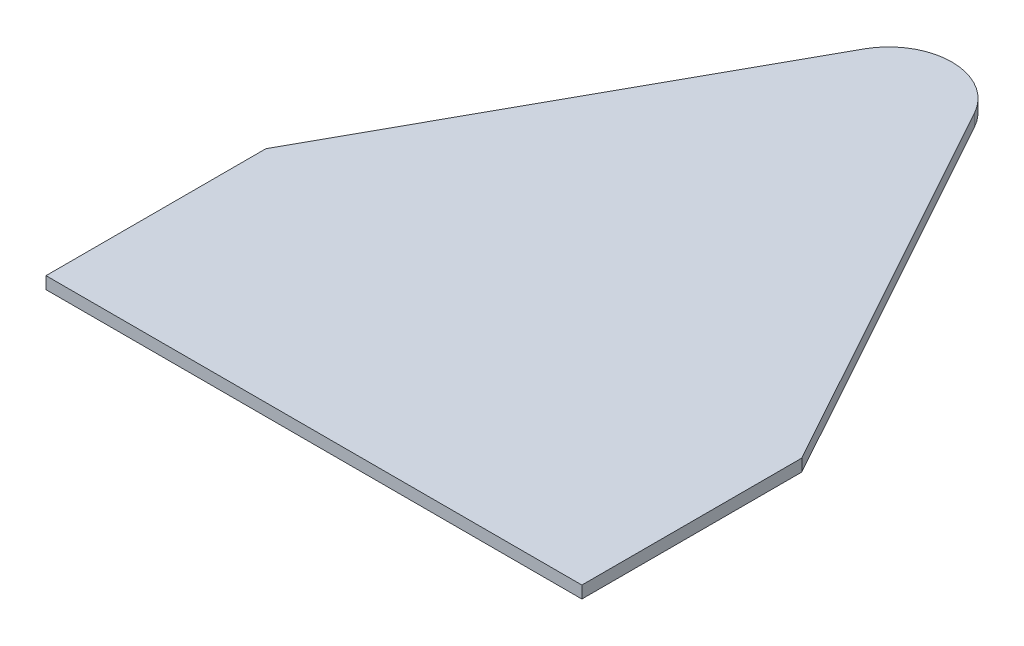
SolidWorks part; units mm, degrees
ref_plane "Front Plane" through (0, 0, 0) normal (0, 0, 1) x (1, 0, 0)
ref_plane "Top Plane" through (0, 0, 0) normal (0, 1, 0) x (1, 0, 0)
ref_plane "Right Plane" through (0, 0, 0) normal (1, 0, 0) x (0, 0, -1)
sketch "Sketch1" plane through (0, 0, 0) normal (0, 1, 0) x (1, 0, 0)
  line L0 (-11.385, 124.53) -> (-55.125, 45.25)
  line L1 (-55.125, 45.25) -> (-55.125, 0)
  line L2 (-55.125, 0) -> (55.125, 0)
  line L3 (55.125, 0) -> (55.125, 45.25)
  line L4 (55.125, 45.25) -> (11.385, 124.53)
  arc A0 (11.385, 124.53) -> (-11.385, 124.53) centre (0, 118.2545) ccw
  point P8 (0, 0)
  dimension "D5" = 13
  dimension "D1" = 110.25
  dimension "D2" = 45.25
  dimension "D3" = 79.28
  dimension "D4" = 43.74
extrude "Boss-Extrude1" add sketch "Sketch1" along normal blind 2.5
